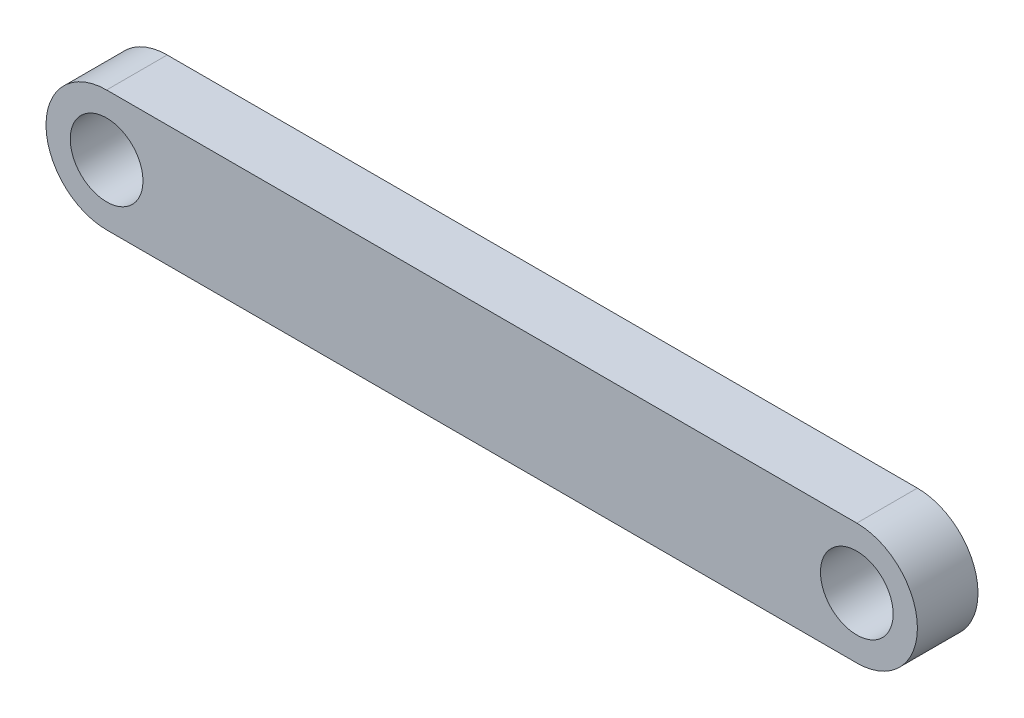
SolidWorks part; units mm, degrees
ref_plane "Front Plane" through (0, 0, 0) normal (0, 0, 1) x (1, 0, 0)
ref_plane "Top Plane" through (0, 0, 0) normal (0, 1, 0) x (1, 0, 0)
ref_plane "Right Plane" through (0, 0, 0) normal (1, 0, 0) x (0, 0, -1)
sketch "Sketch1" plane through (0, 0, 0) normal (0, 0, 1) x (1, 0, 0)
  line L0 (30.95, 0) -> (-30.95, 0) construction
  line L1 (30.95, -5) -> (-30.95, -5)
  line L2 (30.95, 5) -> (-30.95, 5)
  arc A0 (30.95, -5) -> (30.95, 5) centre (30.95, 0) ccw
  arc A1 (-30.95, 5) -> (-30.95, -5) centre (-30.95, 0) ccw
  circle A2 centre (-30.95, 0) radius 3
  circle A3 centre (30.95, 0) radius 3
  point P2 (0, 0)
  dimension "D2" = 5
  dimension "D3" = 6
  dimension "D4" = 6
  dimension "D1" = 61.9
extrude "Boss-Extrude1" add sketch "Sketch1" along normal blind 5
